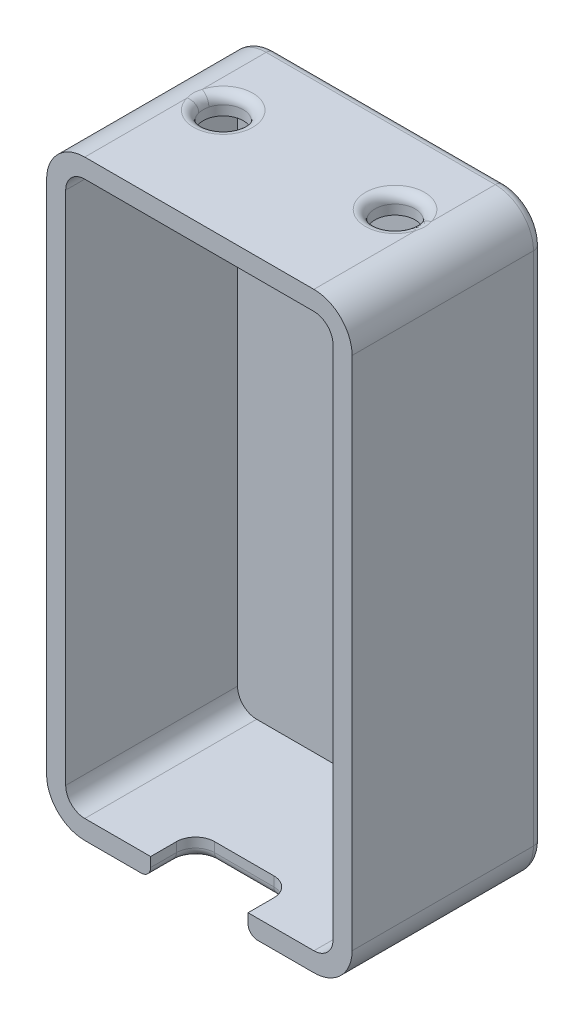
SolidWorks part; units mm, degrees
ref_plane "Front Plane" through (0, 0, 0) normal (0, 0, 1) x (1, 0, 0)
ref_plane "Top Plane" through (0, 0, 0) normal (0, 1, 0) x (1, 0, 0)
ref_plane "Right Plane" through (0, 0, 0) normal (1, 0, 0) x (0, 0, -1)
sketch "Sketch1" plane through (0, 0, 0) normal (0, 0, 1) x (1, 0, 0)
  line L7 (-16, 31) -> (16, 31)
  line L8 (-16, 31) -> (-16, -31)
  line L9 (-16, -31) -> (16, -31)
  line L10 (16, 31) -> (16, -31)
  line L11 (-16, 31) -> (16, -31) construction
  line L12 (-16, -31) -> (16, 31) construction
  point P0 (0, 0)
  point P1 (0, 0)
  point P6 (0, 0)
  dimension "D1" = 32
  dimension "D2" = 62
extrude "Boss-Extrude4" add sketch "Sketch1" along normal blind 2
sketch "Sketch2" plane through (0, 0, 0) normal (0, 0, 1) x (1, 0, 0)
  line L0 (-16, -31) -> (16, -31) construction
  line L17 (-14, 29) -> (14, 29)
  line L18 (-14, 29) -> (-14, -29)
  line L19 (-14, -29) -> (14, -29)
  line L20 (14, 29) -> (14, -29)
  line L23 (-14, 29) -> (14, -29) construction
  line L24 (-14, -29) -> (14, 29) construction
  line L28 (16, -31) -> (16, 31) construction
  line L30 (-16, 31) -> (16, 31)
  line L31 (-16, 31) -> (-16, -31)
  line L32 (-16, -31) -> (16, -31)
  line L33 (16, 31) -> (16, -31)
  point P0 (0, 0)
  point P1 (0, 0)
  point P2 (0, 0)
  point P3 (0, 0)
  dimension "D1" = 2
  dimension "D2" = 2
extrude "Boss-Extrude5" add sketch "Sketch2" against normal blind 18
sketch "Sketch3" plane through (0, 31, 0) normal (0, 1, 0) x (1, 0, 0)
  line L2 (0, 0) -> (0, 6.5)
  line L3 (-9, 6.5) -> (9, 6.5)
  circle A0 centre (-9, 6.5) radius 2.1
  circle A1 centre (9, 6.5) radius 2.1
  point P8 (0, 6.5)
extrude "Cut-Extrude1" cut sketch "Sketch3" against normal blind 10
sketch "Sketch5" plane through (0, -31, 0) normal (0, -1, 0) x (1, 0, 0)
  line L0 (0, -18) -> (0, -13.3) construction
  line L1 (-16, -18) -> (16, -18) construction
  line L2 (5.1, -13.3) -> (-5.1, -13.3)
  line L3 (-5.1, -13.3) -> (-5.1, -18)
  line L4 (-5.1, -18) -> (5.1, -18)
  line L5 (5.1, -18) -> (5.1, -13.3)
  point P8 (0, -13.3)
  dimension "D1" = 10.2
  dimension "D2" = 4.7
extrude "Cut-Extrude2" cut sketch "Sketch5" against normal blind 2
fillet "Fillet13" radius 2 6 edges at (-14, -29, -9) (-14, 29, -9) (14, 29, -9) (14, -29, -9) (-5.1, -30, -13.3) (5.1, -30, -13.3)
fillet "Fillet14" radius 4 4 edges at (16, -31, -8) (16, 31, -8) (-16, 31, -8) (-16, -31, -8)
fillet "Fillet15" radius 1 15 edges at (-14.8284, -29.8284, 2) (-16, 0, 2) (-14.8284, 29.8284, 2) (0, 31, 2) (14.8284, 29.8284, 2) (16, 0, 2) (14.8284, -29.8284, 2) (-5.1, -31, -16.65) (-4.5142, -31, -13.8858) (0, -31, -13.3) (4.5142, -31, -13.8858) (0, -31, 2) (5.1, -31, -16.65) (-9, 31, -4.4) (9, 31, -4.4)
move or copy body "Body-Move/Copy1" bodies to move or copy 122 copy no rotation origin (0, 0, -8) rotation axis (0, 1, 0) rotation angle 180
